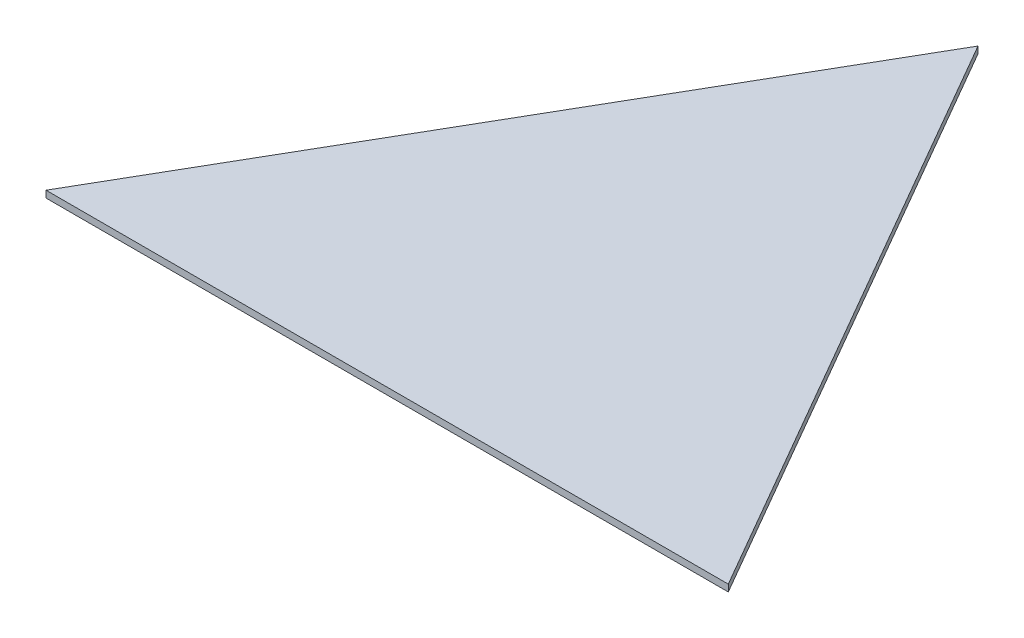
SolidWorks part; units mm, degrees
ref_plane "Front Plane" through (0, 0, 0) normal (0, 0, 1) x (1, 0, 0)
ref_plane "Top Plane" through (0, 0, 0) normal (0, 1, 0) x (1, 0, 0)
ref_plane "Right Plane" through (0, 0, 0) normal (1, 0, 0) x (0, 0, -1)
sketch "Sketch1" plane through (0, 0, 0) normal (0, 1, 0) x (1, 0, 0)
  line L1 (250, -144.3376) -> (0, 288.6751)
  line L2 (0, 288.6751) -> (-250, -144.3376)
  line L3 (-250, -144.3376) -> (250, -144.3376)
  circle A0 centre (0, 0) radius 144.3376 construction
  dimension "D1" = 500
extrude "Boss-Extrude1" add sketch "Sketch1" along normal blind 5
